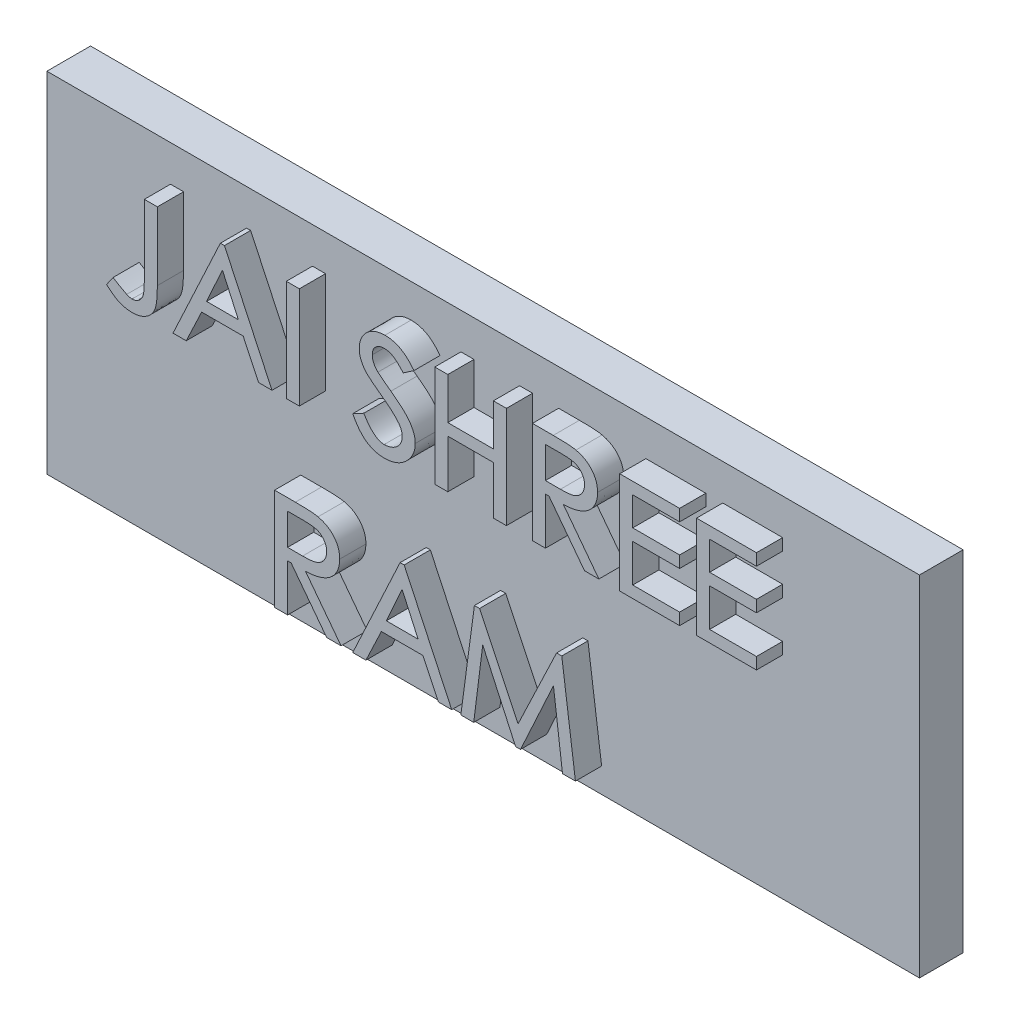
SolidWorks part; units mm, degrees
ref_plane "Front Plane" through (0, 0, 0) normal (0, 0, 1) x (1, 0, 0)
ref_plane "Top Plane" through (0, 0, 0) normal (0, 1, 0) x (1, 0, 0)
ref_plane "Right Plane" through (0, 0, 0) normal (1, 0, 0) x (0, 0, -1)
sketch "Sketch1" plane through (0, 0, 0) normal (0, 0, 1) x (1, 0, 0)
  line L5 (0, 0) -> (50, 0)
  line L6 (0, 0) -> (0, 20)
  line L7 (0, 20) -> (50, 20)
  line L8 (50, 0) -> (50, 20)
  dimension "D1" = 20
  dimension "D2" = 50
extrude "Boss-Extrude4" add sketch "Sketch1" along normal blind 2.5
sketch "Sketch3" plane through (0, 0, 2.5) normal (0, 0, 1) x (1, 0, 0)
  text T0 "JAI SHREE\r\n    RAM" font "Century Gothic" height in points 22
extrude "Boss-Extrude5" add sketch "Sketch3" along normal blind 1.5
